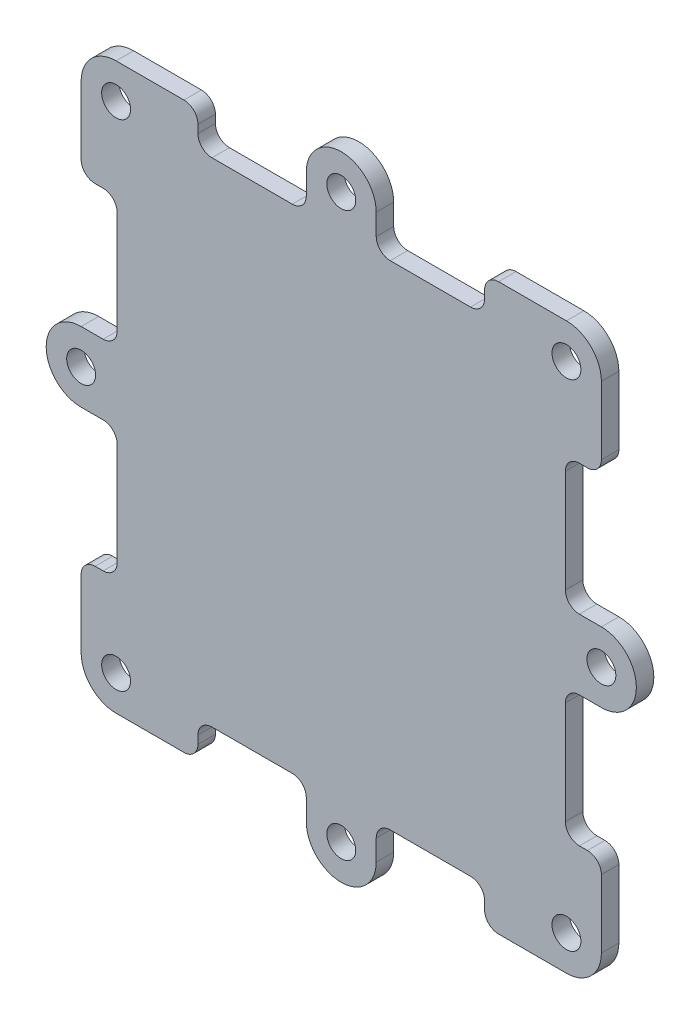
SolidWorks part; units mm, degrees
material "ABS PC"
ref_plane "X-Y Datum" through (0, 0, 0) normal (0, 0, 1) x (1, 0, 0)
ref_plane "X-Z Datum" through (0, 0, 0) normal (0, 1, 0) x (1, 0, 0)
ref_plane "Y-Z Datum" through (0, 0, 0) normal (1, 0, 0) x (0, 0, -1)
sketch "Sketch1" plane through (0, 0, 0) normal (0, 0, 1) x (1, 0, 0)
  line L10 (4.8137, 148.8563) -> (4.8137, 136.525)
  line L11 (23.495, 155.2063) -> (11.1637, 155.2063)
  line L13 (8.8138, 133.985) -> (7.3537, 133.985)
  line L32 (7.3537, 73.787) -> (8.8138, 73.787)
  line L37 (11.3538, 94.996) -> (11.3538, 76.327)
  line L38 (4.8137, 97.536) -> (8.8138, 97.536)
  line L39 (8.8138, 110.236) -> (4.8137, 110.236)
  line L40 (11.3538, 131.445) -> (11.3538, 112.776)
  line L74 (58.42, 52.7558) -> (58.42, 56.5658)
  line L80 (45.72, 56.5658) -> (45.72, 52.7558)
  line L81 (28.575, 59.1058) -> (43.18, 59.1058)
  line L82 (26.035, 55.1057) -> (26.035, 56.5658)
  line L83 (11.1637, 52.5657) -> (23.495, 52.5657)
  line L84 (4.8137, 71.247) -> (4.8137, 58.9157)
  line L112 (99.3263, 58.9157) -> (99.3263, 71.247)
  line L113 (80.645, 52.5657) -> (92.9763, 52.5657)
  line L114 (78.105, 56.5658) -> (78.105, 55.1057)
  line L115 (60.96, 59.1058) -> (75.565, 59.1058)
  line L120 (92.7862, 76.327) -> (92.7862, 94.996)
  line L121 (96.7863, 73.787) -> (95.3262, 73.787)
  line L138 (92.7862, 131.445) -> (92.7862, 112.776)
  line L139 (95.3262, 110.236) -> (99.3263, 110.236)
  line L140 (99.3263, 97.536) -> (95.3262, 97.536)
  line L184 (92.9763, 155.2063) -> (80.645, 155.2063)
  line L185 (99.3263, 136.525) -> (99.3263, 148.8563)
  line L186 (95.3262, 133.985) -> (96.7863, 133.985)
  line L192 (75.565, 148.6662) -> (60.96, 148.6662)
  line L193 (78.105, 152.6663) -> (78.105, 151.2062)
  line L220 (26.035, 152.6663) -> (26.035, 151.2062)
  line L221 (28.575, 148.6662) -> (43.18, 148.6662)
  line L222 (45.72, 151.2062) -> (45.72, 155.0162)
  line L223 (58.42, 155.0162) -> (58.42, 151.2062)
  circle A0 centre (11.1637, 148.8563) radius 2.625
  circle A1 centre (92.9763, 148.8563) radius 2.625
  circle A2 centre (52.07, 155.0162) radius 2.625
  circle A3 centre (99.3263, 103.886) radius 2.625
  circle A4 centre (92.9763, 58.9157) radius 2.625
  circle A5 centre (52.07, 52.7558) radius 2.625
  circle A6 centre (11.1637, 58.9157) radius 2.625
  circle A7 centre (4.8137, 103.886) radius 2.625
  arc A16 (4.8137, 136.525) -> (7.3537, 133.985) centre (7.3537, 136.525) ccw
  arc A17 (11.1637, 155.2063) -> (4.8137, 148.8563) centre (11.1637, 148.8563) ccw
  arc A20 (11.3538, 131.445) -> (8.8138, 133.985) centre (8.8138, 131.445) ccw
  arc A38 (11.3538, 94.996) -> (8.8138, 97.536) centre (8.8138, 94.996) ccw
  arc A39 (4.8137, 110.236) -> (4.8137, 97.536) centre (4.8137, 103.886) ccw
  arc A40 (8.8138, 110.236) -> (11.3538, 112.776) centre (8.8138, 112.776) ccw
  arc A42 (8.8138, 73.787) -> (11.3538, 76.327) centre (8.8138, 76.327) ccw
  arc A81 (60.96, 59.1058) -> (58.42, 56.5658) centre (60.96, 56.5658) ccw
  arc A90 (45.72, 52.7558) -> (58.42, 52.7558) centre (52.07, 52.7558) ccw
  arc A91 (45.72, 56.5658) -> (43.18, 59.1058) centre (43.18, 56.5658) ccw
  arc A92 (28.575, 59.1058) -> (26.035, 56.5658) centre (28.575, 56.5658) ccw
  arc A93 (23.495, 52.5657) -> (26.035, 55.1057) centre (23.495, 55.1057) ccw
  arc A94 (4.8137, 58.9157) -> (11.1637, 52.5657) centre (11.1637, 58.9157) ccw
  arc A95 (7.3537, 73.787) -> (4.8137, 71.247) centre (7.3537, 71.247) ccw
  arc A117 (99.3263, 71.247) -> (96.7863, 73.787) centre (96.7863, 71.247) ccw
  arc A118 (92.9763, 52.5657) -> (99.3263, 58.9157) centre (92.9763, 58.9157) ccw
  arc A119 (78.105, 55.1057) -> (80.645, 52.5657) centre (80.645, 55.1057) ccw
  arc A120 (78.105, 56.5658) -> (75.565, 59.1058) centre (75.565, 56.5658) ccw
  arc A121 (92.7862, 76.327) -> (95.3262, 73.787) centre (95.3262, 76.327) ccw
  arc A145 (95.3262, 133.985) -> (92.7862, 131.445) centre (95.3262, 131.445) ccw
  arc A146 (92.7862, 112.776) -> (95.3262, 110.236) centre (95.3262, 112.776) ccw
  arc A147 (99.3263, 97.536) -> (99.3263, 110.236) centre (99.3263, 103.886) ccw
  arc A148 (95.3262, 97.536) -> (92.7862, 94.996) centre (95.3262, 94.996) ccw
  arc A188 (99.3263, 148.8563) -> (92.9763, 155.2063) centre (92.9763, 148.8563) ccw
  arc A189 (96.7863, 133.985) -> (99.3263, 136.525) centre (96.7863, 136.525) ccw
  arc A198 (75.565, 148.6662) -> (78.105, 151.2062) centre (75.565, 151.2062) ccw
  arc A199 (80.645, 155.2063) -> (78.105, 152.6663) centre (80.645, 152.6663) ccw
  arc A233 (26.035, 152.6663) -> (23.495, 155.2063) centre (23.495, 152.6663) ccw
  arc A234 (26.035, 151.2062) -> (28.575, 148.6662) centre (28.575, 151.2062) ccw
  arc A235 (43.18, 148.6662) -> (45.72, 151.2062) centre (43.18, 151.2062) ccw
  arc A236 (58.42, 155.0162) -> (45.72, 155.0162) centre (52.07, 155.0162) ccw
  arc A237 (58.42, 151.2062) -> (60.96, 148.6662) centre (60.96, 151.2062) ccw
extrude "Boss-Extrude1" add sketch "Sketch1" along normal blind 3.175
